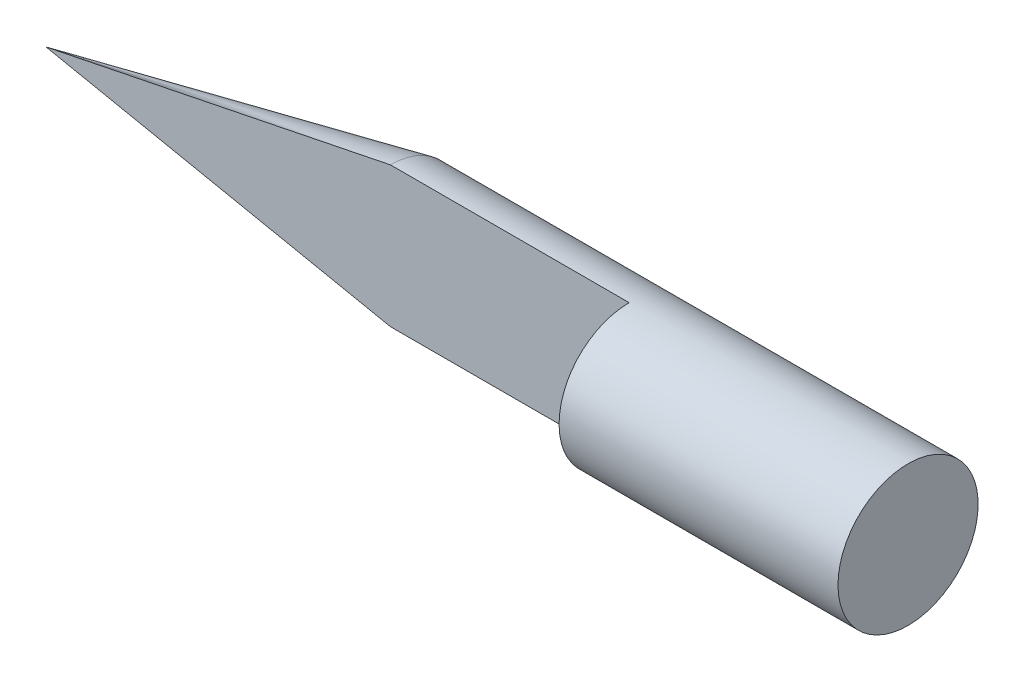
SolidWorks part; units mm, degrees
ref_plane "前基準面" through (0, 0, 0) normal (0, 0, 1) x (1, 0, 0)
ref_plane "上基準面" through (0, 0, 0) normal (0, 1, 0) x (1, 0, 0)
ref_plane "右基準面" through (0, 0, 0) normal (1, 0, 0) x (0, 0, -1)
sketch "草圖1" plane through (0, 0, 0) normal (0, 0, 1) x (1, 0, 0)
  line L0 (0, 0) -> (37.09, 0) construction
  line L1 (14.82, 0) -> (14.82, 3.0152)
  line L2 (0, 0) -> (14.82, 3.0152)
  line L3 (14.82, 3.0152) -> (37.09, 3.0152)
  line L4 (37.09, 3.0152) -> (37.09, -3.0152)
  line L5 (0, 0) -> (14.82, -3.0152)
  line L6 (14.82, -3.0152) -> (37.09, -3.0152)
  point P3 (14.82, 0)
  dimension "D1" = 37.09
  dimension "D2" = 14.82
  dimension "D3" = 11.5
revolve "旋轉1" add sketch "草圖1" angle 180 about L0
sketch "草圖2" plane through (0, 0, 0) normal (0, 0, 1) x (1, 0, 0)
  line L0 (25.0565, 3.0152) -> (25.0565, -3.0152)
  line L1 (14.82, 3.0152) -> (37.09, 3.0152) construction
  line L2 (14.82, -3.0152) -> (37.09, -3.0152) construction
  line L3 (37.09, 0) -> (25.0565, 0) construction
  line L5 (25.0565, 3.0152) -> (37.09, 3.0152)
  line L6 (37.09, 3.0152) -> (37.09, -3.0152)
  line L7 (37.09, -3.0152) -> (25.0565, -3.0152)
  line L8 (25.0565, 0) -> (37.09, 0)
sketch "草圖3" plane through (37.09, 0, 0) normal (1, 0, 0) x (0, 0, -1)
  line L0 (0, 3.0152) -> (0, -3.0152) construction
  circle A0 centre (0, 0) radius 3.0152
extrude "填料-伸長2" add sketch "草圖3" against normal blind 12
